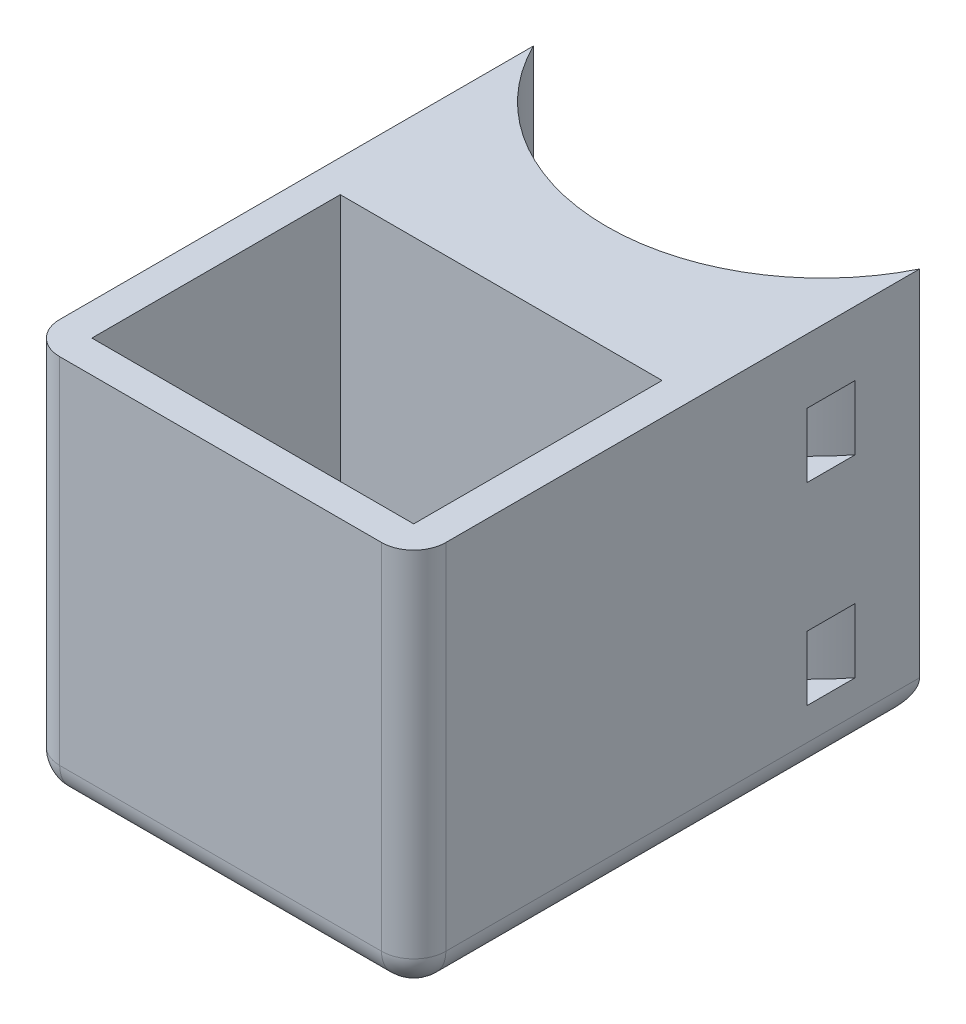
SolidWorks part; units mm, degrees
ref_plane "Front Plane" through (0, 0, 0) normal (0, 0, 1) x (1, 0, 0)
ref_plane "Top Plane" through (0, 0, 0) normal (0, 1, 0) x (1, 0, 0)
ref_plane "Right Plane" through (0, 0, 0) normal (1, 0, 0) x (0, 0, -1)
sketch "Sketch2" plane through (0, 0, 0) normal (0, 1, 0) x (1, 0, 0)
  line L0 (0, -55) -> (0, 55) construction
  line L1 (-76.2, -76.2) -> (76.2, -76.2)
  line L2 (-76.2, -76.2) -> (-76.2, 76.2)
  line L3 (-76.2, 76.2) -> (76.2, 76.2)
  line L4 (76.2, -76.2) -> (76.2, 76.2)
  line L5 (-55, 0) -> (55, 0) construction
  line L6 (-76.2, 76.2) -> (-76.2, 123.4235)
  line L7 (76.2, 76.2) -> (76.2, 123.4235)
  arc A0 (-76.2, 123.4235) -> (76.2, 123.4235) centre (0, 161.29) ccw
  dimension "D5" = 170.18
  dimension "D1" = 152.4
  dimension "D2" = 152.4
  dimension "D3" = 76.2
  dimension "D4" = 76.2
  dimension "D6" = 85.09
extrude "Boss-Extrude1" add sketch "Sketch2" along normal blind 25.4 contours A0 L3 L7 | A0 L6 L3 | L1 L4 L3 L2
sketch "Sketch3" plane through (0, 25.4, 0) normal (0, 1, 0) x (1, 0, 0)
  line L0 (-76.2, 123.4235) -> (-76.2, -76.2)
  line L1 (-76.2, -76.2) -> (76.2, -76.2)
  line L2 (76.2, -76.2) -> (76.2, 123.4235)
  arc A0 (-76.2, 123.4235) -> (76.2, 123.4235) centre (0, 161.29) ccw
  arc A1 (-76.2, 98.0235) -> (76.2, 98.0235) centre (0, 157.3741) ccw
  arc A2 (-76.2, 78.9735) -> (76.2, 78.9735) centre (0, 153.634) ccw
  arc M5 (76.2, 123.4235) -> (-76.2, 123.4235) centre (0, 161.29) cw
  line M6 (-76.2, 123.4235) -> (-76.2, -76.2)
  line M7 (-76.2, -76.2) -> (76.2, -76.2)
  line M8 (76.2, -76.2) -> (76.2, 123.4235)
  dimension "D3" = 96.5864
  dimension "4.2" = 106.68
  dimension "D1" = 25.4
  dimension "D2" = 25.4
  dimension "D4" = 19.05
  dimension "D5" = 19.05
extrude "Boss-Extrude2" add sketch "Sketch3" along normal blind 101.6 contours A1 L2 M6 M5 | A2 M6 M7 M8
sketch "Sketch4" plane through (0, 127, 0) normal (0, 1, 0) x (1, 0, 0)
  line L0 (-76.2, 123.4235) -> (-76.2, -76.2)
  line L1 (-76.2, -76.2) -> (76.2, -76.2)
  line L2 (76.2, -76.2) -> (76.2, 123.4235)
  arc A0 (-76.2, 123.4235) -> (76.2, 123.4235) centre (0, 161.29) ccw
sketch "Sketch5" plane through (0, 0, 0) normal (0, 1, 0) x (1, 0, 0)
  line L0 (-76.2, 123.4235) -> (-76.2, -76.2)
  line L1 (-76.2, -76.2) -> (76.2, -76.2)
  line L2 (76.2, -76.2) -> (76.2, 123.4235)
  arc A0 (-76.2, 123.4235) -> (76.2, 123.4235) centre (0, 161.29) ccw
extrude "Boss-Extrude5" add sketch "Sketch5" along normal blind 50.8 from offset 50.8
extrude "Boss-Extrude6" add sketch "Sketch4" along normal blind 25.4 contours L0 L1 L2 A0
sketch "Sketch6" plane through (0, 152.4, 0) normal (0, 1, 0) x (1, 0, 0)
  line L0 (-76.2, 123.4235) -> (-76.2, -76.2) construction
  line L1 (-63.5, -63.5) -> (63.5, -63.5)
  line L2 (-63.5, -63.5) -> (-63.5, 34.5235)
  line L3 (-63.5, 34.5235) -> (63.5, 34.5235)
  line L4 (63.5, -63.5) -> (63.5, 34.5235)
  line L5 (76.2, -76.2) -> (76.2, 123.4235) construction
  line L6 (-76.2, -76.2) -> (76.2, -76.2) construction
  dimension "D1" = 12.7
  dimension "D2" = 12.7
  dimension "D3" = 12.7
  dimension "D4" = 88.9
extrude "Cut-Extrude1" cut sketch "Sketch6" against normal blind 139.7
sketch "Sketch7" plane through (0, 12.7, 0) normal (0, 1, 0) x (1, 0, 0)
  line L0 (0, -83.82) -> (0, 83.82) construction
  line L1 (-63.5, -63.5) -> (63.5, -63.5) construction
  line L2 (-63.5, -63.5) -> (63.5, -63.5) construction
  circle A0 centre (-13.0048, -50.8) radius 8.255
  circle A1 centre (13.0048, -50.8) radius 8.255
  dimension "D1" = 16.51
  dimension "D2" = 16.51
  dimension "D3" = 26.0096
  dimension "D4" = 13.0048
  dimension "D5" = 12.7
  dimension "D6" = 12.7
extrude "Cut-Extrude2" cut sketch "Sketch7" against normal blind 12.7
chamfer "Chamfer1" distance 7.62 angle 20 2 edges at (-13.0048, 0, 59.055) (13.0048, 0, 59.055)
fillet "Fillet1" radius 12.7 5 edges at (-76.2, 0, -23.6118) (76.2, 0, -23.6118) (76.2, 76.2, 76.2) (0, 0, 76.2) (-76.2, 76.2, 76.2)
